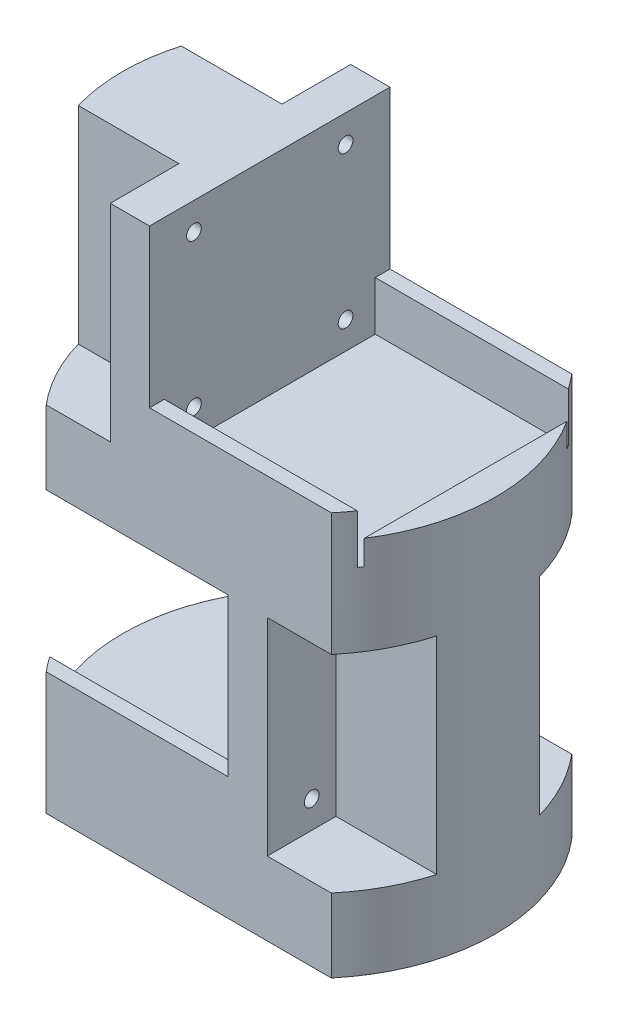
SolidWorks part; units mm, degrees
ref_plane "Front Plane" through (0, 0, 0) normal (0, 0, 1) x (1, 0, 0)
ref_plane "Top Plane" through (0, 0, 0) normal (0, 1, 0) x (1, 0, 0)
ref_plane "Right Plane" through (0, 0, 0) normal (1, 0, 0) x (0, 0, -1)
sketch "Sketch1" plane through (0, 0, 0) normal (0, 1, 0) x (1, 0, 0)
  line L1 (-38, -21.5) -> (38, -21.5)
  line L2 (-38, -21.5) -> (-38, 21.5)
  line L3 (-38, 21.5) -> (38, 21.5)
  line L4 (38, -21.5) -> (38, 21.5)
  line L5 (-38, -21.5) -> (38, 21.5) construction
  line L6 (-38, 21.5) -> (38, -21.5) construction
  point P0 (0, 0)
  dimension "D1" = 76
  dimension "D2" = 43
sketch "Sketch2" plane through (0, 0, 0) normal (0, 1, 0) x (1, 0, 0)
  circle A0 centre (0, 0) radius 38
  dimension "D1" = 76
extrude "Boss-Extrude1" add sketch "Sketch1" along normal blind 15 contours L4 L3 L2 L1
sketch "Sketch3" plane through (0, 15, 0) normal (0, 1, 0) x (1, 0, 0)
  line L0 (68, -21.5) -> (68, 21.5) construction
  line L1 (68, -21.5) -> (8, -21.5) construction
  line L2 (68, 21.5) -> (8, 21.5) construction
  line L3 (8, -21.5) -> (8, 21.5)
  line L4 (68, -21.5) -> (8, 21.5) construction
  line L5 (68, 21.5) -> (8, -21.5) construction
  line L6 (8, 21.5) -> (38, 21.5)
  line L7 (38, 21.5) -> (38, -21.5)
  line L8 (38, -21.5) -> (8, -21.5)
  point P1 (38, 0)
  dimension "D1" = 43
  dimension "D2" = 30
extrude "Boss-Extrude2" add sketch "Sketch3" along normal blind 42.1
sketch "Sketch4" plane through (0, 15, 0) normal (0, 1, 0) x (1, 0, 0)
  line L4 (-38, -21.5) -> (38, -21.5)
  line L5 (-38, 21.5) -> (-38, -21.5)
  line L6 (38, 21.5) -> (-38, 21.5)
  line L7 (38, -21.5) -> (38, 21.5)
  line L8 (-38, -21.5) -> (38, -21.5)
  line L9 (-38, 21.5) -> (-38, -21.5)
  line L10 (38, 21.5) -> (-38, 21.5)
  line L11 (38, -21.5) -> (38, 21.5)
  dimension "D1" = 0
extrude "Boss-Extrude3" add sketch "Sketch4" along normal blind 15 from surface at 42.1 starting at face at (23, 57.1, 0)
sketch "Sketch5" plane through (0, 72.1, 0) normal (0, 1, 0) x (1, 0, 0)
  line L0 (-38, -21.5) -> (38, -21.5) construction
  line L1 (-38, 21.5) -> (-8, 21.5)
  line L2 (-38, 21.5) -> (-38, -21.5)
  line L3 (-38, -21.5) -> (-8, -21.5)
  line L4 (-8, 21.5) -> (-8, -21.5)
  dimension "D1" = 30
extrude "Boss-Extrude4" add sketch "Sketch5" along normal blind 42.1
sketch "Sketch6" plane through (0, 0, 21.5) normal (0, 0, 1) x (1, 0, 0)
  line L0 (-38, 114.2) -> (-38, 57.1) construction
  line L1 (-38, 0) -> (38, 0) construction
  line L4 (-8, 114.2) -> (-8, 72.1) construction
  line L6 (-38, 57.1) -> (8, 57.1) construction
  line L7 (-38, 114.2) -> (-8, 114.2) construction
  line L8 (-38, 0) -> (38, 0)
  line L9 (-38, 25) -> (-38, 0)
  line L10 (38, 82.1) -> (38, 0)
  line L11 (-8, 114.2) -> (-8, 82.1)
  line L12 (8, 57.1) -> (8, 25)
  line L13 (-38, 57.1) -> (8, 57.1)
  line L14 (-38, 114.2) -> (-38, 57.1)
  line L15 (-38, 114.2) -> (-8, 114.2)
  line L22 (-8, 82.1) -> (38, 82.1)
  line L23 (-8, 82.1) -> (38, 82.1)
  line L25 (-38, 25) -> (8, 25)
  line L26 (-38, 25) -> (8, 25)
  dimension "D1" = 10
  dimension "D2" = 10
extrude "Boss-Extrude5" add sketch "Sketch6" along normal blind 3
sketch "Sketch7" plane through (0, 0, -21.5) normal (0, 0, -1) x (-1, 0, 0)
  line L2 (8, 82.1) -> (-38, 82.1) construction
  line L3 (-38, 82.1) -> (-38, 72.1) construction
  line L4 (-38, 0) -> (38, 0) construction
  line L5 (38, 0) -> (38, 15) construction
  line L7 (-8, 15) -> (-8, 57.1) construction
  line L8 (-8, 57.1) -> (38, 57.1) construction
  line L9 (38, 57.1) -> (38, 114.2) construction
  line L10 (38, 114.2) -> (8, 114.2) construction
  line L11 (8, 114.2) -> (8, 72.1) construction
  line L13 (-38, 72.1) -> (-38, 0) construction
  line L14 (38, 25) -> (-8, 25) construction
  line L17 (38, 15) -> (38, 25) construction
  line L18 (-38, 0) -> (38, 0)
  line L19 (38, 0) -> (38, 15)
  line L21 (-8, 25) -> (-8, 57.1)
  line L22 (-8, 57.1) -> (38, 57.1)
  line L23 (38, 57.1) -> (38, 114.2)
  line L24 (38, 114.2) -> (8, 114.2)
  line L25 (8, 114.2) -> (8, 82.1)
  line L27 (-38, 72.1) -> (-38, 0)
  line L28 (38, 25) -> (-8, 25)
  line L31 (38, 15) -> (38, 25)
  line L34 (8, 82.1) -> (-38, 82.1)
  line L35 (-38, 82.1) -> (-38, 72.1)
extrude "Boss-Extrude6" add sketch "Sketch7" along normal blind 3
extrude "Cut-Extrude1" cut sketch "Sketch2" along normal through all flip side to cut contours A0
sketch "Sketch8" plane through (0, 72.1, 0) normal (0, 1, 0) x (1, 0, 0)
  line L1 (31.9, -20.6492) -> (31.9, 20.6492)
  arc A0 (31.3329, -21.5) -> (31.3329, 21.5) centre (0, 0) ccw construction
  arc A1 (31.9, -20.6492) -> (31.9, 20.6492) centre (0, 0) ccw
  point P0 (38, 0)
  point P10 (31.9, 0)
  dimension "D1" = 6.1
extrude "Boss-Extrude7" add sketch "Sketch8" along normal blind 5
sketch "Sketch9" plane through (0, 0, 0) normal (1, 0, 0) x (0, 0, -1)
  line L0 (-24.5, 0) -> (-24.5, 82.1) construction
  line L1 (-24.5, 15) -> (-10.5, 15)
  line L2 (-24.5, 15) -> (-24.5, 57.1)
  line L3 (-24.5, 57.1) -> (-10.5, 57.1)
  line L4 (-10.5, 15) -> (-10.5, 57.1)
  line L5 (-24.5, 0) -> (24.5, 0) construction
  line L8 (0, 41.8) -> (0, -41.8) construction
  line L9 (24.5, 15) -> (10.5, 15)
  line L10 (24.5, 15) -> (24.5, 57.1)
  line L11 (24.5, 57.1) -> (10.5, 57.1)
  line L12 (10.5, 15) -> (10.5, 57.1)
  dimension "D1" = 15
  dimension "D2" = 14
  dimension "D3" = 42.1
extrude "Cut-Extrude2" cut sketch "Sketch9" along normal blind 40 from offset 16
sketch "Sketch10" plane through (-8, 0, 0) normal (1, 0, 0) x (0, 0, -1)
  line L1 (-24.5, 114.2) -> (-10.5, 114.2)
  line L2 (-24.5, 114.2) -> (-24.5, 72.1)
  line L3 (-24.5, 72.1) -> (-10.5, 72.1)
  line L4 (-10.5, 114.2) -> (-10.5, 72.1)
  line L5 (0, 41.8) -> (0, -41.8) construction
  line L6 (24.5, 72.1) -> (10.5, 72.1)
  line L7 (10.5, 114.2) -> (10.5, 72.1)
  line L8 (24.5, 114.2) -> (10.5, 114.2)
  line L9 (24.5, 114.2) -> (24.5, 72.1)
  dimension "D1" = 42.1
  dimension "D2" = 14
extrude "Cut-Extrude3" cut sketch "Sketch10" against normal blind 40 from offset 8 offset against normal yes
sketch "Sketch11" plane through (16, 0, 0) normal (1, 0, 0) x (0, 0, -1)
  line L0 (-24.5, 57.1) -> (-24.5, 15) construction
  line L1 (24.5, 15) -> (24.5, 57.1) construction
  line L2 (-24.5, 15) -> (-10.5, 15) construction
  circle A0 centre (-15.45, 20.6) radius 1.5
  circle A1 centre (15.45, 20.6) radius 1.5
  circle A2 centre (15.45, 51.5) radius 1.5
  circle A3 centre (-15.45, 51.5) radius 1.5
  dimension "D1" = 3
  dimension "D5" = 9.05
  dimension "D7" = 30.9
  dimension "D4" = 9.05
  dimension "D6" = 5.6
  dimension "D2" = 2
  dimension "D3" = 2
extrude "Cut-Extrude4" cut sketch "Sketch11" against normal blind 60
sketch "Sketch12" plane through (-8, 0, 0) normal (1, 0, 0) x (0, 0, -1)
  line L0 (-44.4205, 64.6) -> (67.4104, 64.6)
  line L1 (24.5, 57.1) -> (10.5, 57.1) construction
  dimension "D1" = 7.5
  dimension "D2" = 111.8309
ref_plane "Plane1" through (0, 64.6, 0) normal (0, 1, 0) x (1, 0, 0)
mirror "Mirror1" about plane through (0, 64.6, 0) normal (0, 1, 0) of "Cut-Extrude4"
ref_plane "Plane2" through (-38.52, 0, 0) normal (1, 0, 0) x (0, 0, -1)
